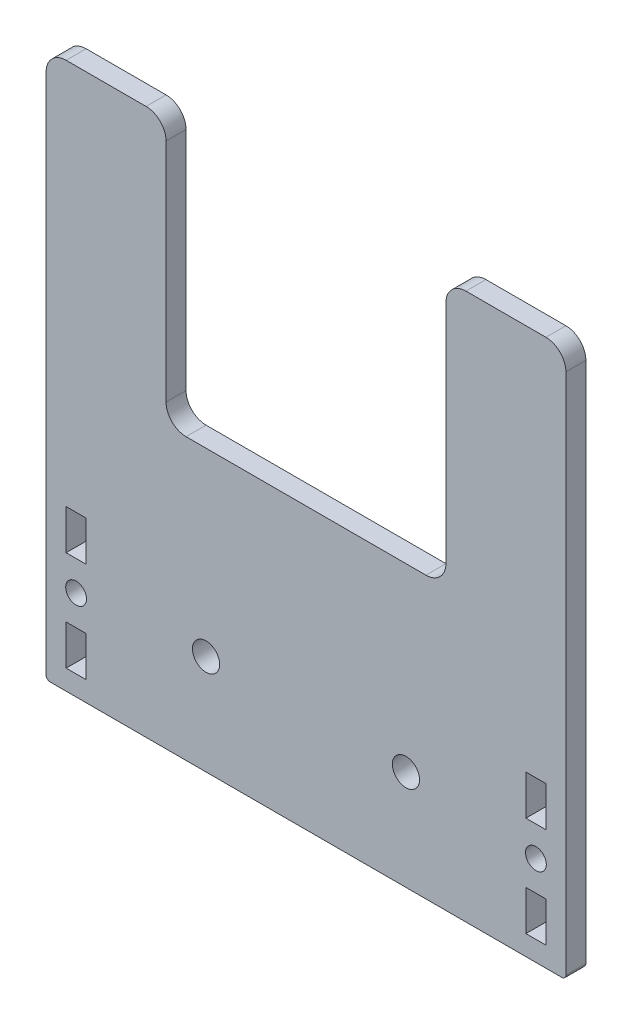
SolidWorks part; units mm, degrees
ref_plane "Front Plane" through (0, 0, 0) normal (0, 0, 1) x (1, 0, 0)
ref_plane "Top Plane" through (0, 0, 0) normal (0, 1, 0) x (1, 0, 0)
ref_plane "Right Plane" through (0, 0, 0) normal (1, 0, 0) x (0, 0, -1)
sketch "Sketch1" plane through (0, 0, 0) normal (0, 0, 1) x (1, 0, 0)
  line L0 (0, 68.3333) -> (0, -68.3333) construction
  line L1 (-65, 68.3333) -> (65, 68.3333)
  line L2 (-65, 68.3333) -> (-65, -68.3333)
  line L3 (-65, -68.3333) -> (65, -68.3333)
  line L4 (65, 68.3333) -> (65, -68.3333)
  line L5 (-65, 0) -> (65, 0) construction
  circle A0 centre (-25, -43.3333) radius 3.4
  circle A1 centre (-25, 104.6667) radius 3.4 construction
  circle A2 centre (25, 104.6667) radius 3.4 construction
  circle A3 centre (25, -43.3333) radius 3.4
  dimension "D2" = 25
  dimension "D3" = 6.8
  dimension "D4" = 25
  dimension "D5" = 148
  dimension "D1" = 136.6667
  dimension "D6" = 130
extrude "Boss-Extrude1" add sketch "Sketch1" along normal blind 5
sketch "Sketch2" plane through (0, 0, 5) normal (0, 0, 1) x (1, 0, 0)
  line L0 (0, 68.3333) -> (0, -68.3333) construction
  line L1 (-35, 111.8978) -> (35, 111.8978)
  line L2 (-35, 111.8978) -> (-35, 1.8031)
  line L3 (-35, 1.8031) -> (35, 1.8031)
  line L4 (35, 111.8978) -> (35, 1.8031)
  line L5 (65, 68.3333) -> (-65, 68.3333) construction
  line L6 (-65, -68.3333) -> (65, -68.3333) construction
  line L8 (-55, -38.3333) -> (-55, -28.3333)
  line L9 (-60, -28.3333) -> (-55, -28.3333)
  line L10 (-60, -38.3333) -> (-60, -28.3333)
  line L11 (-50, -45.8333) -> (-65, -45.8333) construction
  line L12 (-60, -53.3333) -> (-55, -53.3333)
  line L13 (-60, -53.3333) -> (-60, -63.3333)
  line L14 (-60, -63.3333) -> (-55, -63.3333)
  line L15 (50, -53.3333) -> (50, 53.3333)
  line L16 (50, 53.3333) -> (-50, 53.3333)
  line L17 (-50, 53.3333) -> (-50, -53.3333)
  line L18 (-50, -53.3333) -> (50, -53.3333)
  line L19 (50, -53.3333) -> (50, 53.3333) construction
  line L20 (50, 53.3333) -> (-50, 53.3333) construction
  line L21 (-50, 53.3333) -> (-50, -53.3333) construction
  line L22 (-50, -53.3333) -> (50, -53.3333) construction
  line L23 (-55, -53.3333) -> (-55, -63.3333)
  line L24 (-65, 68.3333) -> (-65, -68.3333) construction
  line L25 (-60, -38.3333) -> (-55, -38.3333)
  line L26 (57.5, -45.8333) -> (57.5, -63.3333) construction
  line L27 (60, -38.3333) -> (55, -38.3333)
  line L28 (55, -53.3333) -> (55, -63.3333)
  line L29 (60, -63.3333) -> (55, -63.3333)
  line L30 (60, -53.3333) -> (60, -63.3333)
  line L31 (60, -53.3333) -> (55, -53.3333)
  line L32 (60, -38.3333) -> (60, -28.3333)
  line L33 (60, -28.3333) -> (55, -28.3333)
  line L34 (55, -38.3333) -> (55, -28.3333)
  circle A0 centre (-57.5, -45.8333) radius 2.6
  circle A1 centre (57.5, -45.8333) radius 2.6
  dimension "D7" = 5.2
  dimension "D1" = 15
  dimension "D2" = 15
  dimension "D3" = 5
  dimension "D4" = 10
  dimension "D5" = 5
  dimension "D6" = 17.5
  dimension "D8" = 10
extrude "Cut-Extrude1" cut sketch "Sketch2" against normal blind 5
fillet "Fillet1" radius 5 6 edges at (65, 68.3333, 2.5) (35, 68.3333, 2.5) (35, 1.8031, 2.5) (-35, 1.8031, 2.5) (-35, 68.3333, 2.5) (-65, 68.3333, 2.5)
fillet "Fillet2" radius 1 2 edges at (65, -68.3333, 2.5) (-65, -68.3333, 2.5)
